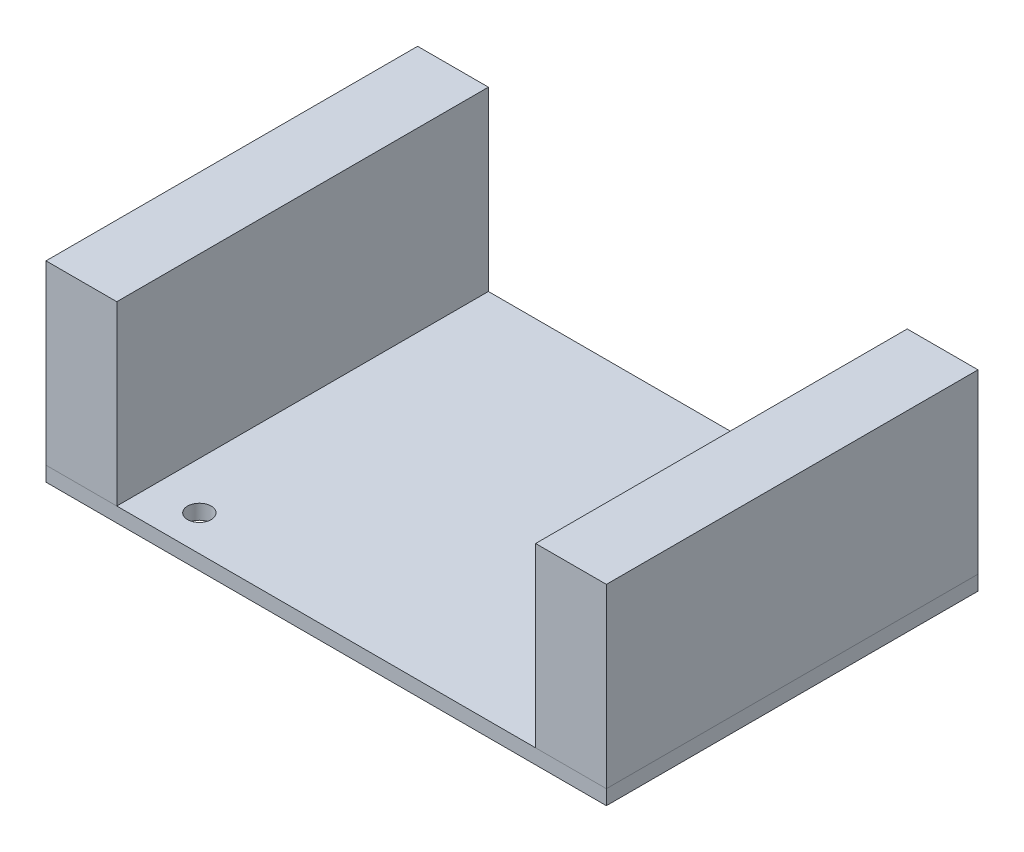
SolidWorks part; units mm, degrees
ref_plane "Front Plane" through (0, 0, 0) normal (0, 0, 1) x (1, 0, 0)
ref_plane "Top Plane" through (0, 0, 0) normal (0, 1, 0) x (1, 0, 0)
ref_plane "Right Plane" through (0, 0, 0) normal (1, 0, 0) x (0, 0, -1)
sketch "Sketch1" plane through (0, 0, 0) normal (0, 1, 0) x (1, 0, 0)
  line L1 (-23.75, 15.75) -> (23.75, 15.75)
  line L2 (-23.75, 15.75) -> (-23.75, -15.75)
  line L3 (-23.75, -15.75) -> (23.75, -15.75)
  line L4 (23.75, 15.75) -> (23.75, -15.75)
  line L5 (-23.75, 15.75) -> (23.75, -15.75) construction
  line L6 (-23.75, -15.75) -> (23.75, 15.75) construction
  circle A0 centre (13.75, 12.75) radius 1
  circle A1 centre (-13.75, -12.75) radius 1
  point P0 (0, 0)
  dimension "D7" = 2
  dimension "D1" = 47.5
  dimension "D2" = 31.5
  dimension "D3" = 3
  dimension "D4" = 3
  dimension "D5" = 10
  dimension "D6" = 10
extrude "Boss-Extrude1" add sketch "Sketch1" along normal blind 1.25
sketch "Sketch2" plane through (0, 1.25, 0) normal (0, 1, 0) x (1, 0, 0)
  line L0 (-23.75, -15.75) -> (23.75, -15.75) construction
  line L1 (-23.75, 15.75) -> (-17.75, 15.75)
  line L2 (-23.75, 15.75) -> (-23.75, -15.75)
  line L3 (-23.75, -15.75) -> (-17.75, -15.75)
  line L4 (-17.75, 15.75) -> (-17.75, -15.75)
  line L6 (23.75, 15.75) -> (17.75, 15.75)
  line L7 (23.75, 15.75) -> (23.75, -15.75)
  line L8 (23.75, -15.75) -> (17.75, -15.75)
  line L9 (17.75, 15.75) -> (17.75, -15.75)
  dimension "D1" = 6
  dimension "D2" = 6
extrude "Boss-Extrude2" add sketch "Sketch2" along normal blind 15 separate body
